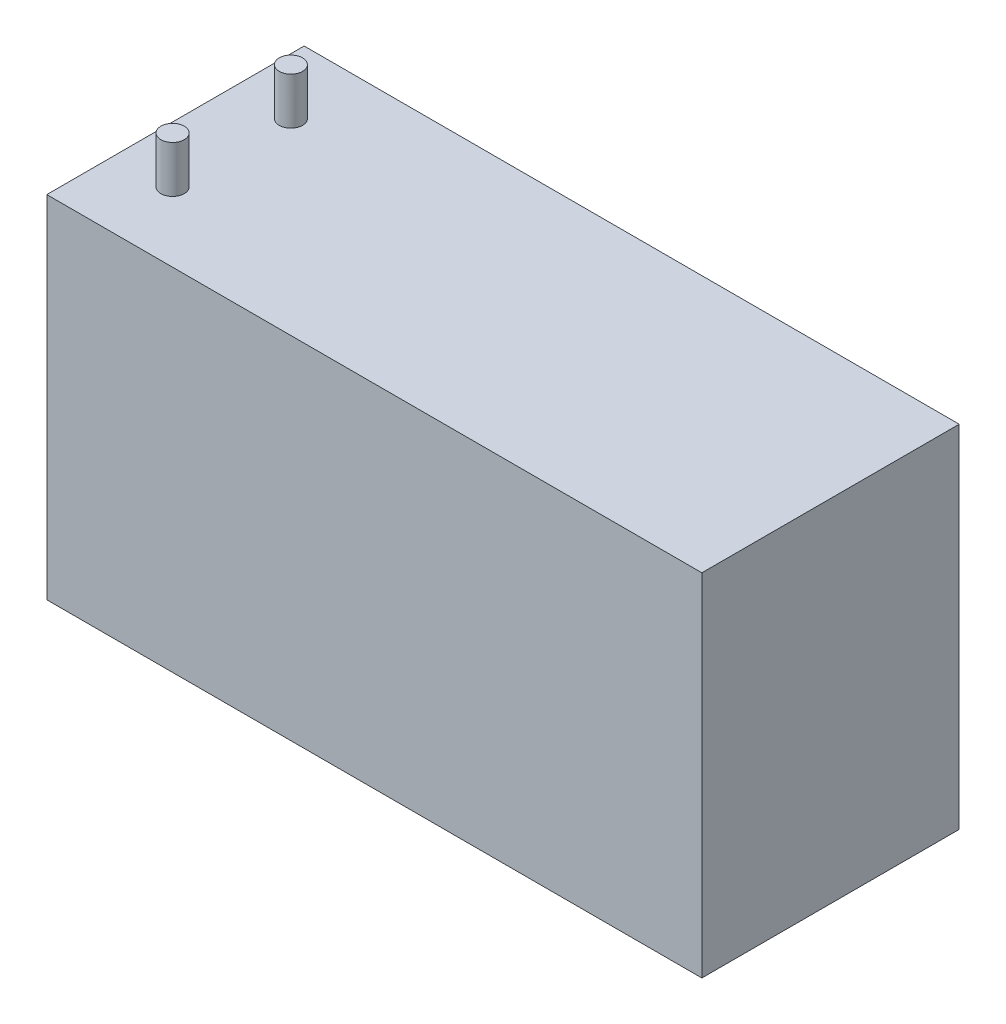
SolidWorks part; units mm, degrees
ref_plane "前视基准面" through (0, 0, 0) normal (0, 0, 1) x (1, 0, 0)
ref_plane "上视基准面" through (0, 0, 0) normal (0, 1, 0) x (1, 0, 0)
ref_plane "右视基准面" through (0, 0, 0) normal (1, 0, 0) x (0, 0, -1)
sketch "草图1" plane through (0, 0, 0) normal (0, 0, 1) x (1, 0, 0)
  line L1 (-14, -7.5) -> (14, -7.5)
  line L2 (-14, -7.5) -> (-14, 7.5)
  line L3 (-14, 7.5) -> (14, 7.5)
  line L4 (14, -7.5) -> (14, 7.5)
  line L5 (-14, -7.5) -> (14, 7.5) construction
  line L6 (-14, 7.5) -> (14, -7.5) construction
  point P0 (0, 0)
  dimension "D1" = 28
  dimension "D2" = 15
extrude "凸台-拉伸1" add sketch "草图1" along normal blind 11
sketch "草图2" plane through (0, 7.5, 0) normal (0, 1, 0) x (1, 0, 0)
  line L0 (-14, -5.5) -> (14, -5.5) construction
  line L1 (-14, -11) -> (-14, 0) construction
  line L2 (14, -11) -> (14, 0) construction
  circle A0 centre (-11.5946, -2.9718) radius 0.5
  circle A2 centre (-11.5946, -8.0282) radius 0.5
  dimension "D1" = 1
extrude "凸台-拉伸2" add sketch "草图2" along normal blind 2
